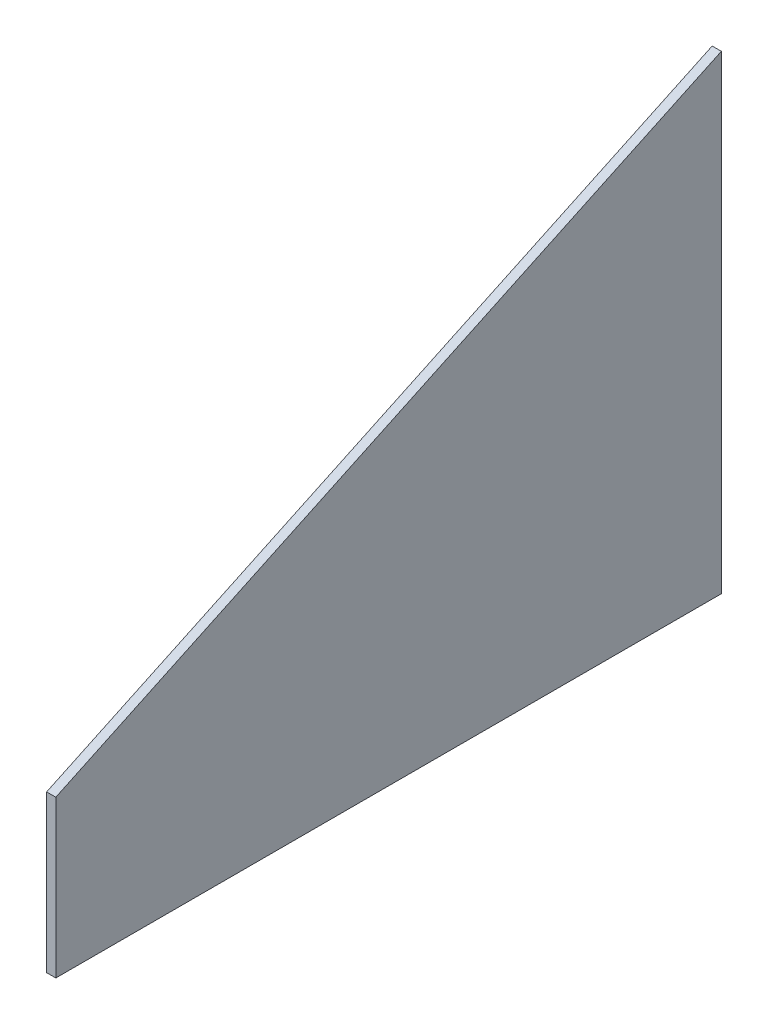
SolidWorks part; units mm, degrees
ref_plane "Front Plane" through (0, 0, 0) normal (0, 0, 1) x (1, 0, 0)
ref_plane "Top Plane" through (0, 0, 0) normal (0, 1, 0) x (1, 0, 0)
ref_plane "Right Plane" through (0, 0, 0) normal (1, 0, 0) x (0, 0, -1)
sketch "Sketch1" plane through (0, 0, 0) normal (1, 0, 0) x (0, 0, -1)
  line L0 (0, 0) -> (863.6, 0)
  line L1 (863.6, 0) -> (863.6, 609.6)
  line L2 (0, 0) -> (0, 203.2)
  line L3 (863.6, 609.6) -> (0, 203.2)
  dimension "D1" = 863.6
  dimension "D2" = 609.6
  dimension "D3" = 203.2
extrude "Boss-Extrude1" add sketch "Sketch1" along normal blind 11.9062 contours L3 L2 L0 L1
